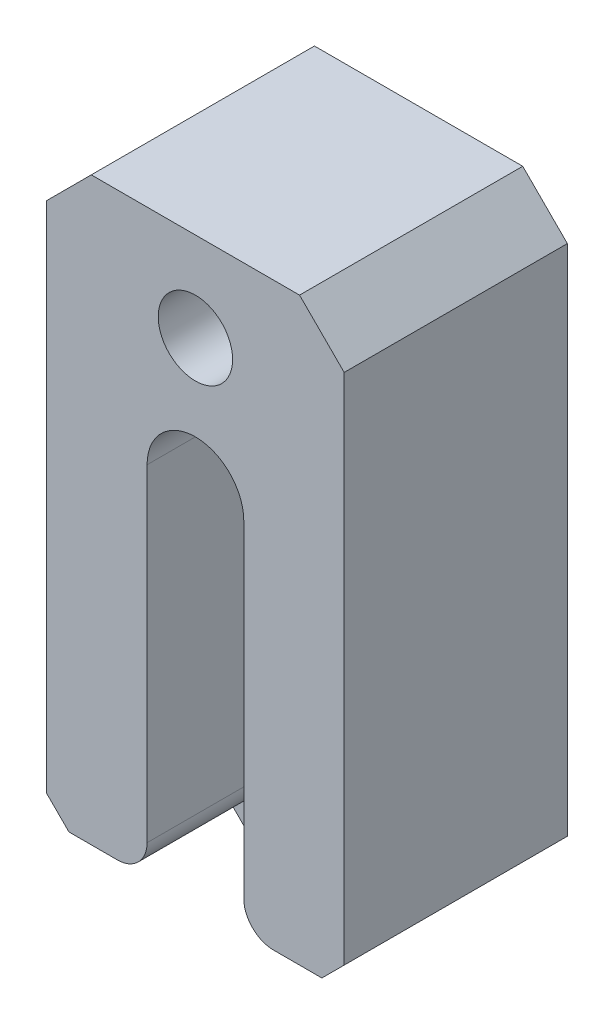
SolidWorks part; units mm, degrees
ref_plane "Plan de face" through (0, 0, 0) normal (0, 0, 1) x (1, 0, 0)
ref_plane "Plan de dessus" through (0, 0, 0) normal (0, 1, 0) x (1, 0, 0)
ref_plane "Plan de droite" through (0, 0, 0) normal (1, 0, 0) x (0, 0, -1)
sketch "Esquisse1" plane through (0, 0, 0) normal (0, 0, 1) x (1, 0, 0)
  line L1 (0, 0) -> (20, 0)
  line L2 (0, 0) -> (0, 45)
  line L3 (0, 45) -> (20, 45)
  line L4 (20, 0) -> (20, 45)
  dimension "D1" = 20
  dimension "D2" = 45
extrude "Boss.-Extru.1" add sketch "Esquisse1" along normal blind 15
sketch "Esquisse2" plane through (0, 0, 15) normal (0, 0, 1) x (1, 0, 0)
  line L0 (10, 0) -> (10, 45) construction
  line L1 (0, 0) -> (20, 0) construction
  line L2 (20, 45) -> (0, 45) construction
  line L3 (10, 12) -> (10, 30) construction
  line L4 (6.75, 12) -> (6.75, 30)
  line L5 (13.25, 12) -> (13.25, 30)
  arc A0 (6.75, 12) -> (13.25, 12) centre (10, 12) ccw
  arc A1 (13.25, 30) -> (6.75, 30) centre (10, 30) ccw
  circle A2 centre (10, 39) radius 2.5
  point P8 (10, 21)
  dimension "D4" = 5
  dimension "D1" = 6.5
  dimension "D2" = 18
  dimension "D3" = 12
  dimension "D5" = 6
extrude "Enlèv. mat.-Extru.1" cut sketch "Esquisse2" against normal up to vertex (15 mm away) up to point (20, 45, 0)
sketch "Esquisse3" plane through (0, 0, 15) normal (0, 0, 1) x (1, 0, 0)
  line L0 (0, 6) -> (20, 6)
  line L1 (0, 45) -> (0, 0) construction
  line L2 (20, 0) -> (20, 45) construction
  line L3 (20, 6) -> (20, 0)
  line L4 (20, 0) -> (0, 0)
  line L5 (0, 0) -> (0, 6)
  dimension "D1" = 6
extrude "Enlèv. mat.-Extru.2" cut sketch "Esquisse3" against normal blind 9
sketch "Esquisse6" plane through (0, 0, 15) normal (0, 0, 1) x (1, 0, 0)
  line L0 (7.5, 0) -> (0, 7.5)
  line L1 (0, 0) -> (20, 0) construction
  line L2 (0, 45) -> (0, 6) construction
  line L3 (0, 7.5) -> (0, -7.5)
  line L4 (0, -7.5) -> (20, -7.5)
  line L5 (20, -7.5) -> (20, 7.5)
  line L6 (20, 7.5) -> (12.5, 0)
  line L7 (12.5, 0) -> (7.5, 0)
  line L8 (10, 8.75) -> (10, 0) construction
  line L9 (20, 6) -> (20, 45) construction
  arc A0 (6.75, 12) -> (13.25, 12) centre (10, 12) ccw construction
  dimension "D1" = 5
  dimension "D2" = 15
extrude "Enlèv. mat.-Extru.3" cut sketch "Esquisse6" against normal up to vertex (15 mm away) up to point (20, 0, 0)
sketch "Esquisse7" plane through (0, 0, 15) normal (0, 0, 1) x (1, 0, 0)
  line L0 (6.75, 30) -> (6.75, 12) construction
  line L1 (6.75, 14) -> (13.25, 14)
  line L2 (6.75, 14) -> (6.75, 6)
  line L3 (6.75, 6) -> (13.25, 6)
  line L4 (13.25, 14) -> (13.25, 6)
  line L5 (18.5, 6) -> (1.5, 6) construction
  line L6 (13.25, 12) -> (13.25, 30) construction
  dimension "D1" = 8
extrude "Enlèv. mat.-Extru.4" cut sketch "Esquisse7" against normal up to vertex (9 mm away) up to point (12.5, 0, 6)
fillet "Congé1" radius 2 2 edges at (13.25, 6, 10.5) (6.75, 6, 10.5)
chamfer "Chanfrein1" distance 3 angle 45 2 edges at (20, 45, 7.5) (0, 45, 7.5)
